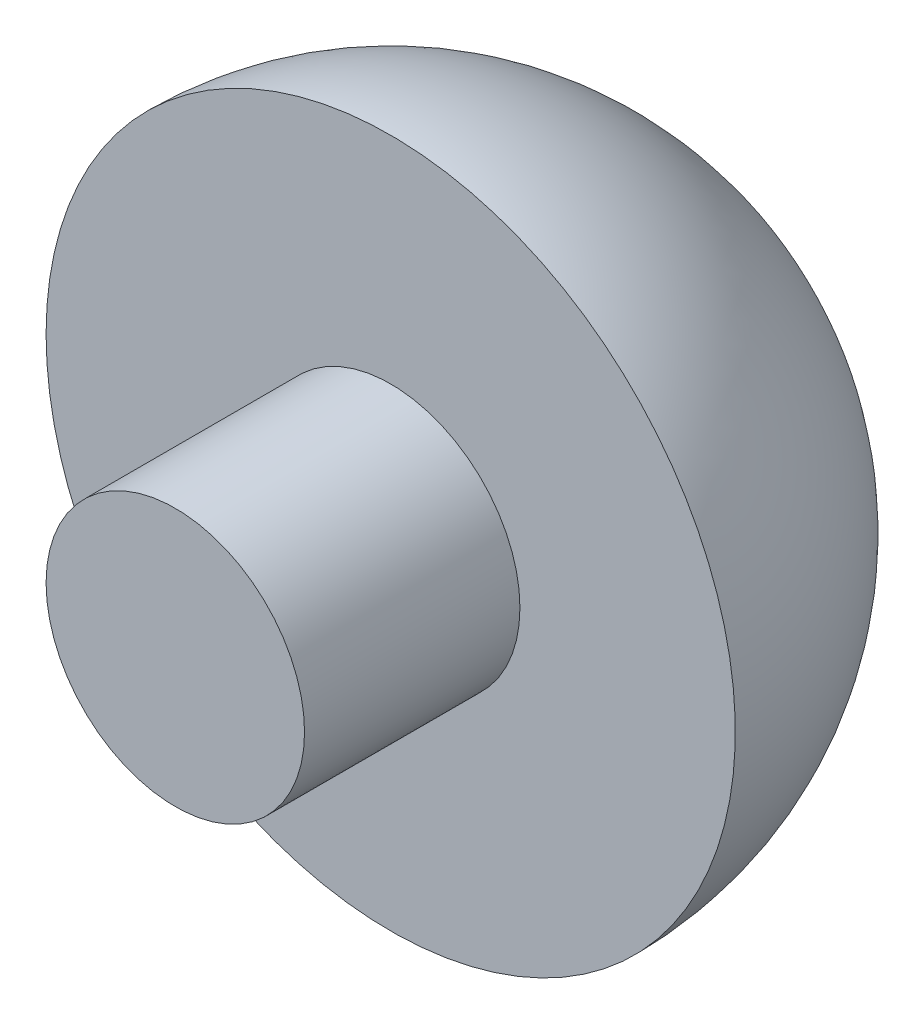
SolidWorks part; units mm, degrees
material "PE Low/Medium Density"
ref_plane "Plano frontal" through (0, 0, 0) normal (0, 0, 1) x (1, 0, 0)
ref_plane "Plano superior" through (0, 0, 0) normal (0, 1, 0) x (1, 0, 0)
ref_plane "Plano direito" through (0, 0, 0) normal (1, 0, 0) x (0, 0, -1)
sketch "Sketch1" plane through (0, 0, 0) normal (0, 0, 1) x (1, 0, 0)
  line L0 (0, -16) -> (0, 16)
  arc A0 (0, -16) -> (0, 16) centre (0, 0) ccw
  dimension "D1" = 32
revolve "Revolve1" add sketch "Sketch1" angle 180 about L0
sketch "Sketch4" plane through (0, 0, 0) normal (0, 0, 1) x (1, 0, 0)
  circle A0 centre (0, 0) radius 6
  dimension "D1" = 12
extrude "Boss-Extrude1" add sketch "Sketch4" along normal blind 10
